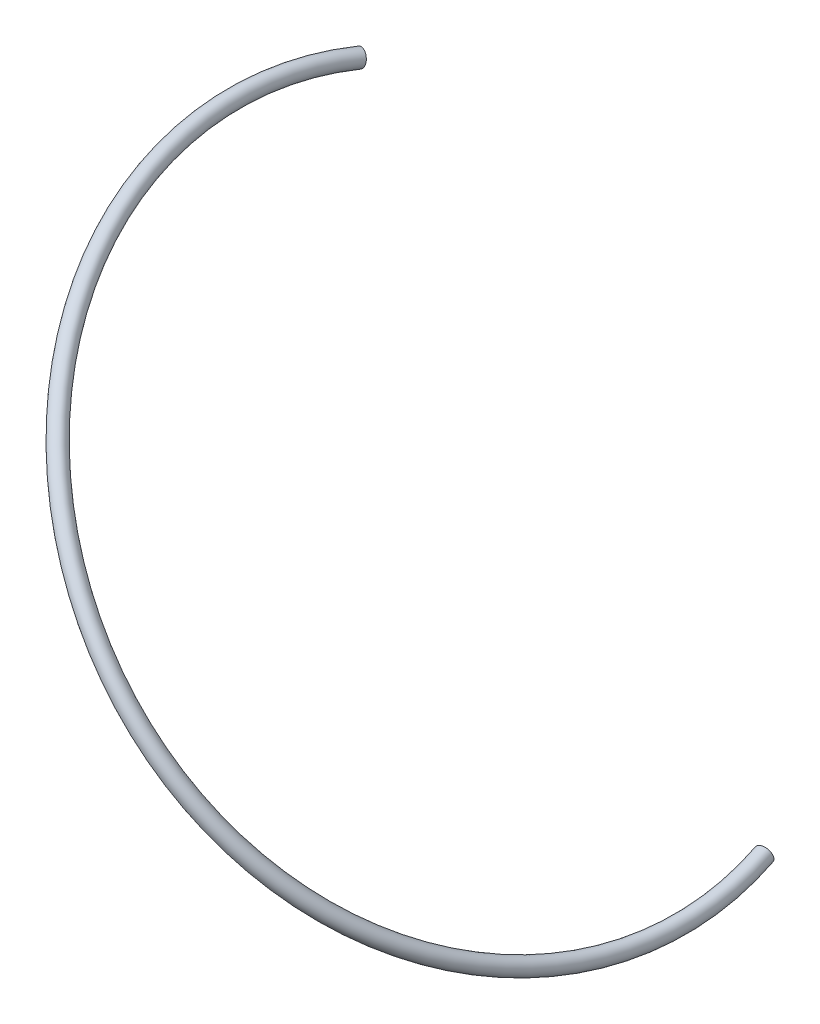
SolidWorks part; units mm, degrees
material "PVC 0.007 Plasticized"
ref_plane "Front Plane" through (0, 0, 0) normal (0, 0, 1) x (1, 0, 0)
ref_plane "Top Plane" through (0, 0, 0) normal (0, 1, 0) x (1, 0, 0)
ref_plane "Right Plane" through (0, 0, 0) normal (1, 0, 0) x (0, 0, -1)
sketch3d "3DSketch1"
  circle A0 centre (137.5, 25.85, 22.25) radius 3.5 construction
  circle A1 centre (137.5, 25.85, 22.25) radius 3.5 construction
  circle A2 centre (240.75, -88.2, 27) radius 3.5 construction
  circle A3 centre (240.75, -88.2, 27) radius 3.5 construction
  point P2 (137.5, 25.85, 25.75)
  point P4 (137.5, 25.85, 25.75)
  point P7 (240.75, -88.2, 30.5)
  point P9 (240.75, -88.2, 30.5)
  point P10 (137.5, 25.85, 22.25)
  point P11 (240.75, -88.2, 27)
ref_plane "Plane1" through (88.4283, 80.0546, 0) normal (-0.7413, -0.6711, 0) x (0, 0, 1)
sketch "Sketch2" plane through (88.4283, 80.0546, 0) normal (-0.7413, -0.6711, 0) x (0, 0, 1)
  arc A0 (22.25, -73.1175) -> (27, -226.9614) centre (49.5344, -149.2704) cw
  dimension "D1" = 304.8
sweep "Sweep1" add path "Sketch2" circular profile diameter 4 parameters "D3"=4
